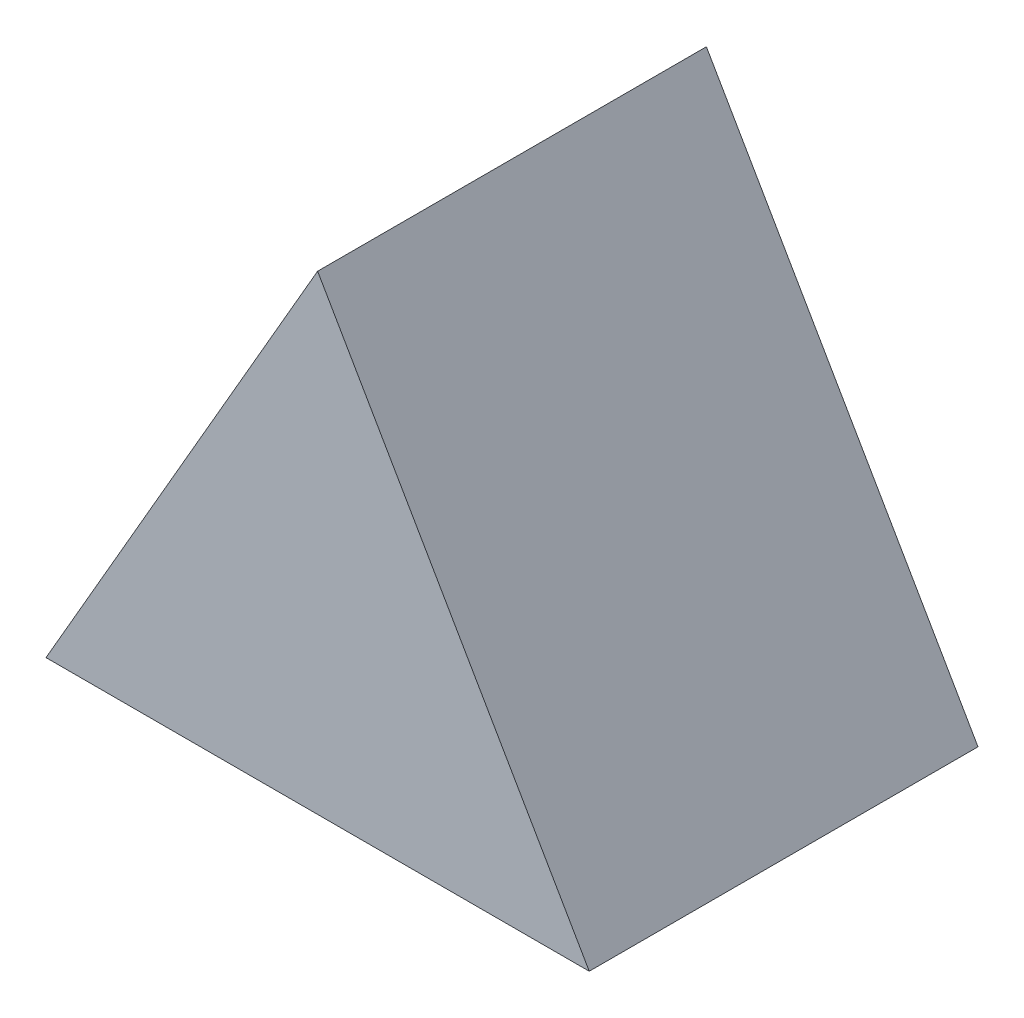
SolidWorks part; units mm, degrees
ref_plane "Спереди" through (0, 0, 0) normal (0, 0, 1) x (1, 0, 0)
ref_plane "Сверху" through (0, 0, 0) normal (0, 1, 0) x (1, 0, 0)
ref_plane "Справа" through (0, 0, 0) normal (1, 0, 0) x (0, 0, -1)
sketch "Эскиз1" plane through (0, 0, 0) normal (0, 0, 1) x (1, 0, 0)
  line L0 (-2.655, -1.516) -> (2.655, -1.516)
  line L1 (2.655, -1.516) -> (0, 3.0826)
  line L2 (0, 3.0826) -> (-2.655, -1.516)
  dimension "D1" = 5.31
  dimension "D2" = 5.31
  dimension "D3" = 5.31
  dimension "D4" = 2.655
  dimension "D5" = 3.0826
extrude "Бобышка-Вытянуть1" add sketch "Эскиз1" along normal blind 3.8
